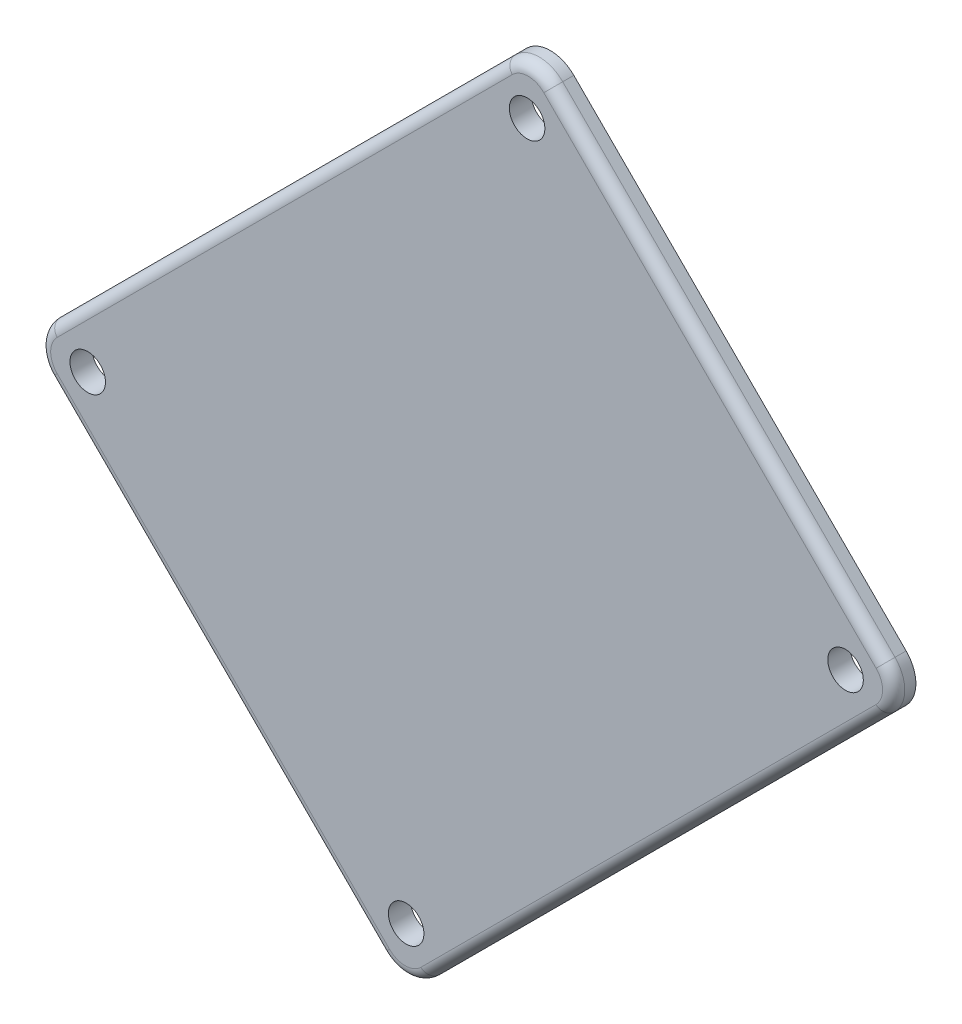
SolidWorks part; units mm, degrees
ref_plane "Front Plane" through (0, 0, 0) normal (0, 0, 1) x (1, 0, 0)
ref_plane "Top Plane" through (0, 0, 0) normal (0, 1, 0) x (1, 0, 0)
ref_plane "Right Plane" through (0, 0, 0) normal (1, 0, 0) x (0, 0, -1)
sketch "Sketch1" plane through (0, 0, 0) normal (0, 0, 1) x (1, 0, 0)
  line L0 (-94.816, -43.9725) -> (-49.5612, 1.2824) construction
  line L1 (-79.7334, -59.055) -> (-109.8986, -28.8899) construction
  line L2 (-64.6438, 16.365) -> (-38.2917, -9.9871) construction
  line L3 (-89.3925, -4.1411) -> (-54.9847, -38.5489) construction
  line L4 (-109.8986, -24.6472) -> (-68.8864, 16.365) construction
  line L5 (-45.387, -28.9513) -> (-75.4908, -59.055) construction
  line L6 (-75.6039, -58.9419) -> (-34.5917, -17.9297)
  line L7 (-79.8466, -58.9419) -> (-109.7855, -29.003)
  line L8 (-34.5917, -13.6871) -> (-64.5306, 16.2518)
  line L9 (-109.7855, -24.7604) -> (-68.7733, 16.2518)
  line L10 (-49.5612, 1.2824) -> (-94.816, -43.9725) construction
  line L11 (-55.0978, -38.4358) -> (-89.2794, -4.2543) construction
  arc A0 (-109.7855, -29.003) -> (-109.7855, -24.7604) centre (-107.6641, -26.8817) cw
  arc A1 (-79.8466, -58.9419) -> (-75.6039, -58.9419) centre (-77.7252, -56.8206) ccw
  arc A2 (-34.5917, -17.9297) -> (-34.5917, -13.6871) centre (-36.7131, -15.8084) ccw
  arc A3 (-64.5306, 16.2518) -> (-68.7733, 16.2518) centre (-66.652, 14.1305) ccw
  point P13 (-72.1886, -21.345)
  dimension "D2" = 3
  dimension "D1" = 48.5
extrude "Boss-Extrude1" add sketch "Sketch1" along normal blind 2
sketch "Sketch2" plane through (0, 0, 2) normal (0, 0, 1) x (1, 0, 0)
  line L0 (-77.6376, -55.4854) -> (-106.329, -26.7941) construction
  line L1 (-106.329, -26.7941) -> (-66.7651, 12.8294) construction
  line L2 (-49.5612, 1.2824) -> (-94.816, -43.9725) construction
  line L3 (-34.5917, -13.6871) -> (-64.5306, 16.2518) construction
  line L4 (-109.7855, -29.003) -> (-79.8466, -58.9419) construction
  line L5 (-89.2794, -4.2543) -> (-55.0978, -38.4358) construction
  line L6 (-68.7733, 16.2518) -> (-109.7855, -24.7604) construction
  line L7 (-75.6039, -58.9419) -> (-34.5917, -17.9297) construction
  circle A0 centre (-106.329, -26.7941) radius 1.6
  circle A1 centre (-77.6376, -55.4854) radius 1.6
  circle A2 centre (-38.0482, -15.896) radius 1.6
  circle A3 centre (-66.7396, 12.7954) radius 1.6
  dimension "D1" = 3.2
extrude "Cut-Extrude1" cut sketch "Sketch2" against normal up to next
fillet "Fillet1" radius 1 8 edges at (-77.7252, -59.8206, 2) (-55.0978, -38.4358, 2) (-33.7131, -15.8084, 2) (-49.5612, 1.2824, 2) (-66.652, 17.1305, 2) (-89.2794, -4.2543, 2) (-110.6641, -26.8817, 2) (-94.816, -43.9725, 2)
